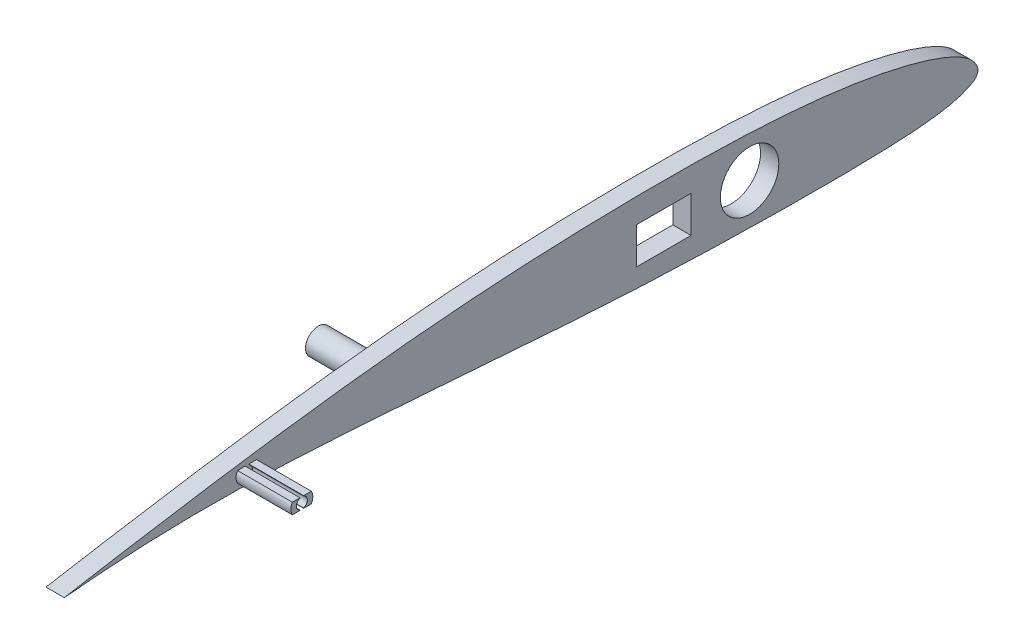
SolidWorks part; units mm, degrees
material "ABS generico"
ref_plane "Piano frontale" through (0, 0, 0) normal (0, 0, 1) x (1, 0, 0)
ref_plane "Piano superiore" through (0, 0, 0) normal (0, 1, 0) x (1, 0, 0)
ref_plane "Piano destro" through (0, 0, 0) normal (1, 0, 0) x (0, 0, -1)
curve "Curva1"
  spline degree 3 poles (0, 0.1724, 248.285) (0, -0.053, 250.4273) (0, 0.2462, 248.3284) (0, 0.5529, 246.6445) (0, 1.2459, 242.6221) (0, 2.0989, 237.7464) (0, 3.1818, 231.3634) (0, 4.2933, 223.9772) (0, 5.7312, 215.5604) (0, 7.1315, 206.3004) (0, 8.6324, 196.1631) (0, 10.1162, 185.3524) (0, 11.5493, 173.9891) (0, 12.8816, 162.1914) (0, 14.0593, 150.0724) (0, 15.0523, 137.7438) (0, 15.8256, 125.3116) (0, 16.3834, 112.8888) (0, 16.7267, 100.597) (0, 16.8648, 88.5669) (0, 16.792, 76.9314) (0, 16.4941, 65.8165) (0, 15.9609, 55.3329) (0, 15.1594, 45.573) (0, 14.0978, 36.6074) (0, 12.7884, 28.4972) (0, 11.2839, 21.2988) (0, 9.6413, 15.0749) (0, 7.9136, 9.8809) (0, 6.1182, 5.7699) (0, 4.2384, 2.7289) (0, 2.3057, 0.8126) (0, 0.7927, 0.0312) (0, -0.4105, -0.0213) (0, -1.7115, 0.4949) (0, -2.8658, 2.6253) (0, -4.0404, 5.6977) (0, -4.9287, 10.0719) (0, -5.5974, 15.6262) (0, -6.0122, 22.4122) (0, -6.265, 30.3619) (0, -6.3814, 39.3972) (0, -6.3554, 49.3987) (0, -6.2185, 60.2453) (0, -5.9476, 71.8018) (0, -5.5368, 83.9408) (0, -4.9386, 96.5461) (0, -4.1527, 109.5201) (0, -3.2196, 122.7671) (0, -2.1909, 136.1764) (0, -1.148, 149.6158) (0, -0.1602, 162.9314) (0, 0.706, 175.9537) (0, 1.3896, 188.4999) (0, 1.8332, 200.3712) (0, 1.9676, 211.3376) (0, 1.8232, 221.1842) (0, 1.4973, 229.6804) (0, 1.0741, 236.8065) (0, 0.6857, 242.1894) (0, 0.3087, 246.5181) (0, 0.1724, 248.285) (0, -0.053, 250.4273) (0, 0.2462, 248.3284) knots -0.014202 -0.006329 -0.001589 0 0.001576 0.006211 0.01368 0.023764 0.036307 0.051658 0.068045 0.086769 0.107053 0.128647 0.151303 0.174786 0.19886 0.223309 0.247929 0.272522 0.296848 0.320648 0.343669 0.365658 0.3864 0.405741 0.423561 0.439779 0.454311 0.467034 0.477831 0.486643 0.493542 0.498786 0.50271 0.50309 0.505896 0.510322 0.516831 0.525521 0.536535 0.549945 0.565696 0.583577 0.603379 0.624844 0.647727 0.671743 0.696673 0.722357 0.748609 0.77521 0.801891 0.828329 0.854175 0.879074 0.902636 0.924421 0.943939 0.960827 0.974827 0.985798 0.993671 0.998411 1 1.001576 1.006211 1.01368 periodic
sketch "Schizzo1" plane through (0, 0, 0) normal (1, 0, 0) x (0, 0, -1)
  line L0 (-250, 0) -> (0.0001, 0.0174) construction
  line L1 (0.0001, 0.0174) -> (-0.0034, 50.0174) construction
  line L2 (-62.4999, 16.3096) -> (-62.4999, -6.155) construction
  line L4 (-78.4999, 10.0773) -> (-93.4999, 10.0773)
  line L5 (-78.4999, 10.0773) -> (-78.4999, 0.0773)
  line L6 (-78.4999, 0.0773) -> (-93.4999, 0.0773)
  line L7 (-93.4999, 10.0773) -> (-93.4999, 0.0773)
  circle A0 centre (-62.4999, 5.0773) radius 8
  spline S0 degree 3 poles (-248.3284, 0.2462) (-250.4273, -0.053) (-248.285, 0.1724) (-246.5181, 0.3087) (-242.1894, 0.6857) (-236.8065, 1.0741) (-229.6804, 1.4973) (-221.1842, 1.8232) (-211.3376, 1.9676) (-200.3712, 1.8332) (-188.4999, 1.3896) (-175.9537, 0.706) (-162.9314, -0.1602) (-149.6158, -1.148) (-136.1764, -2.1909) (-122.7671, -3.2196) (-109.5201, -4.1527) (-96.5461, -4.9386) (-83.9408, -5.5368) (-71.8018, -5.9476) (-60.2453, -6.2185) (-49.3987, -6.3554) (-39.3972, -6.3814) (-30.3619, -6.265) (-22.4122, -6.0122) (-15.6262, -5.5974) (-10.0719, -4.9287) (-5.6977, -4.0404) (-2.6253, -2.8658) (-0.4949, -1.7115) (0.0213, -0.4105) (-0.0312, 0.7927) (-0.8126, 2.3057) (-2.7289, 4.2384) (-5.7699, 6.1182) (-9.8809, 7.9136) (-15.0749, 9.6413) (-21.2988, 11.2839) (-28.4972, 12.7884) (-36.6074, 14.0978) (-45.573, 15.1594) (-55.3329, 15.9609) (-65.8165, 16.4941) (-76.9314, 16.792) (-88.5669, 16.8648) (-100.597, 16.7267) (-112.8888, 16.3834) (-125.3116, 15.8256) (-137.7438, 15.0523) (-150.0724, 14.0593) (-162.1914, 12.8816) (-173.9891, 11.5493) (-185.3524, 10.1162) (-196.1631, 8.6324) (-206.3004, 7.1315) (-215.5604, 5.7312) (-223.9772, 4.2933) (-231.3634, 3.1818) (-237.7464, 2.0989) (-242.6221, 1.2459) (-246.6445, 0.5529) (-248.3284, 0.2462) (-250.4273, -0.053) (-248.285, 0.1724) knots -0.01368 -0.006211 -0.001576 0 0.001589 0.006329 0.014202 0.025173 0.039173 0.056061 0.075579 0.097364 0.120926 0.145825 0.171671 0.198109 0.22479 0.251391 0.277643 0.303327 0.328257 0.352273 0.375156 0.396621 0.416423 0.434304 0.450055 0.463465 0.474479 0.483169 0.489678 0.494104 0.49691 0.49729 0.501214 0.506458 0.513357 0.522169 0.532966 0.545689 0.560221 0.576439 0.594259 0.6136 0.634342 0.656331 0.679352 0.703152 0.727478 0.752071 0.776691 0.80114 0.825214 0.848697 0.871353 0.892947 0.913231 0.931955 0.948342 0.963693 0.976236 0.98632 0.993789 0.998424 1 1.001589 1.006329 1.014202 only from (-250, 0) to (-250, 0) construction
  spline S1 degree 3 poles (-248.3284, 0.2462) (-250.4273, -0.053) (-248.285, 0.1724) (-246.5181, 0.3087) (-242.1894, 0.6857) (-236.8065, 1.0741) (-229.6804, 1.4973) (-221.1842, 1.8232) (-211.3376, 1.9676) (-200.3712, 1.8332) (-188.4999, 1.3896) (-175.9537, 0.706) (-162.9314, -0.1602) (-149.6158, -1.148) (-136.1764, -2.1909) (-122.7671, -3.2196) (-109.5201, -4.1527) (-96.5461, -4.9386) (-83.9408, -5.5368) (-71.8018, -5.9476) (-60.2453, -6.2185) (-49.3987, -6.3554) (-39.3972, -6.3814) (-30.3619, -6.265) (-22.4122, -6.0122) (-15.6262, -5.5974) (-10.0719, -4.9287) (-5.6977, -4.0404) (-2.6253, -2.8658) (-0.4949, -1.7115) (0.0213, -0.4105) (-0.0312, 0.7927) (-0.8126, 2.3057) (-2.7289, 4.2384) (-5.7699, 6.1182) (-9.8809, 7.9136) (-15.0749, 9.6413) (-21.2988, 11.2839) (-28.4972, 12.7884) (-36.6074, 14.0978) (-45.573, 15.1594) (-55.3329, 15.9609) (-65.8165, 16.4941) (-76.9314, 16.792) (-88.5669, 16.8648) (-100.597, 16.7267) (-112.8888, 16.3834) (-125.3116, 15.8256) (-137.7438, 15.0523) (-150.0724, 14.0593) (-162.1914, 12.8816) (-173.9891, 11.5493) (-185.3524, 10.1162) (-196.1631, 8.6324) (-206.3004, 7.1315) (-215.5604, 5.7312) (-223.9772, 4.2933) (-231.3634, 3.1818) (-237.7464, 2.0989) (-242.6221, 1.2459) (-246.6445, 0.5529) (-248.3284, 0.2462) (-250.4273, -0.053) (-248.285, 0.1724) knots -0.01368 -0.006211 -0.001576 0 0.001589 0.006329 0.014202 0.025173 0.039173 0.056061 0.075579 0.097364 0.120926 0.145825 0.171671 0.198109 0.22479 0.251391 0.277643 0.303327 0.328257 0.352273 0.375156 0.396621 0.416423 0.434304 0.450055 0.463465 0.474479 0.483169 0.489678 0.494104 0.49691 0.49729 0.501214 0.506458 0.513357 0.522169 0.532966 0.545689 0.560221 0.576439 0.594259 0.6136 0.634342 0.656331 0.679352 0.703152 0.727478 0.752071 0.776691 0.80114 0.825214 0.848697 0.871353 0.892947 0.913231 0.931955 0.948342 0.963693 0.976236 0.98632 0.993789 0.998424 1 1.001589 1.006329 1.014202 only from (-250, 0) to (-250, 0)
  point P11 (-78.4999, 5.0773)
  dimension "D3" = 16
  dimension "D1" = 50
  dimension "D2" = 62.5
  dimension "D4" = 15
  dimension "D5" = 10
  dimension "D6" = 16
extrude "CorpoFoam" add sketch "Schizzo1" along normal blind 5
sketch "Schizzo2" plane through (0, 0, 0) normal (-1, 0, 0) x (0, 0, 1)
  circle A0 centre (160.4999, 6.0773) radius 3.5
  circle A1 centre (62.4999, 5.0773) radius 8 construction
  dimension "D1" = 7
  dimension "D2" = 98
  dimension "D3" = 1
extrude "PernoAggancio" add sketch "Schizzo2" along normal blind 15
sketch "Schizzo3" plane through (5, 0, 0) normal (1, 0, 0) x (0, 0, -1)
  line L0 (-200, 8.0593) -> (-200, 1.7757) construction
  line L1 (-200.5, 6.4175) -> (-199.5, 3.4175) construction
  line L2 (-197.4019, 6.4175) -> (-199.5, 6.4175)
  line L4 (-197.4019, 3.4175) -> (-199.5, 3.4175)
  line L7 (-200.5, 6.4175) -> (-200.5, 6.3317)
  line L9 (-199.5, 6.4175) -> (-199.5, 6.3317)
  line L10 (-199.5, 6.4175) -> (-200.5, 3.4175) construction
  line L11 (-200.5, 6.4175) -> (-202.5981, 6.4175)
  line L12 (-200.5, 3.4175) -> (-202.5981, 3.4175)
  line L13 (-199.5, 3.5033) -> (-199.5, 3.4175)
  line L14 (-200.5, 3.5033) -> (-200.5, 3.4175)
  arc A0 (-200.5, 6.3317) -> (-200.5, 3.5033) centre (-200, 4.9175) ccw
  arc A1 (-202.5981, 6.4175) -> (-202.5981, 3.4175) centre (-200, 4.9175) ccw
  arc A2 (-197.4019, 3.4175) -> (-197.4019, 6.4175) centre (-200, 4.9175) ccw
  arc A3 (-199.5, 3.5033) -> (-199.5, 6.3317) centre (-200, 4.9175) ccw
  spline S0 degree 3 poles (-248.3284, 0.2462) (-250.4273, -0.053) (-248.285, 0.1724) (-246.5181, 0.3087) (-242.1894, 0.6857) (-236.8065, 1.0741) (-229.6804, 1.4973) (-221.1842, 1.8232) (-211.3376, 1.9676) (-200.3712, 1.8332) (-188.4999, 1.3896) (-175.9537, 0.706) (-162.9314, -0.1602) (-149.6158, -1.148) (-136.1764, -2.1909) (-122.7671, -3.2196) (-109.5201, -4.1527) (-96.5461, -4.9386) (-83.9408, -5.5368) (-71.8018, -5.9476) (-60.2453, -6.2185) (-49.3987, -6.3554) (-39.3972, -6.3814) (-30.3619, -6.265) (-22.4122, -6.0122) (-15.6262, -5.5974) (-10.0719, -4.9287) (-5.6977, -4.0404) (-2.6253, -2.8658) (-0.4949, -1.7115) (0.0213, -0.4105) (-0.0312, 0.7927) (-0.8126, 2.3057) (-2.7289, 4.2384) (-5.7699, 6.1182) (-9.8809, 7.9136) (-15.0749, 9.6413) (-21.2988, 11.2839) (-28.4972, 12.7884) (-36.6074, 14.0978) (-45.573, 15.1594) (-55.3329, 15.9609) (-65.8165, 16.4941) (-76.9314, 16.792) (-88.5669, 16.8648) (-100.597, 16.7267) (-112.8888, 16.3834) (-125.3116, 15.8256) (-137.7438, 15.0523) (-150.0724, 14.0593) (-162.1914, 12.8816) (-173.9891, 11.5493) (-185.3524, 10.1162) (-196.1631, 8.6324) (-206.3004, 7.1315) (-215.5604, 5.7312) (-223.9772, 4.2933) (-231.3634, 3.1818) (-237.7464, 2.0989) (-242.6221, 1.2459) (-246.6445, 0.5529) (-248.3284, 0.2462) (-250.4273, -0.053) (-248.285, 0.1724) knots -0.01368 -0.006211 -0.001576 0 0.001589 0.006329 0.014202 0.025173 0.039173 0.056061 0.075579 0.097364 0.120926 0.145825 0.171671 0.198109 0.22479 0.251391 0.277643 0.303327 0.328257 0.352273 0.375156 0.396621 0.416423 0.434304 0.450055 0.463465 0.474479 0.483169 0.489678 0.494104 0.49691 0.49729 0.501214 0.506458 0.513357 0.522169 0.532966 0.545689 0.560221 0.576439 0.594259 0.6136 0.634342 0.656331 0.679352 0.703152 0.727478 0.752071 0.776691 0.80114 0.825214 0.848697 0.871353 0.892947 0.913231 0.931955 0.948342 0.963693 0.976236 0.98632 0.993789 0.998424 1 1.001589 1.006329 1.014202 only from (-250, 0) to (-250, 0) construction
  dimension "D1" = 3
  dimension "D2" = 6
  dimension "D3" = 50
  dimension "D4" = 1
extrude "PernoAggancioAlettone" add sketch "Schizzo3" along normal blind 15
